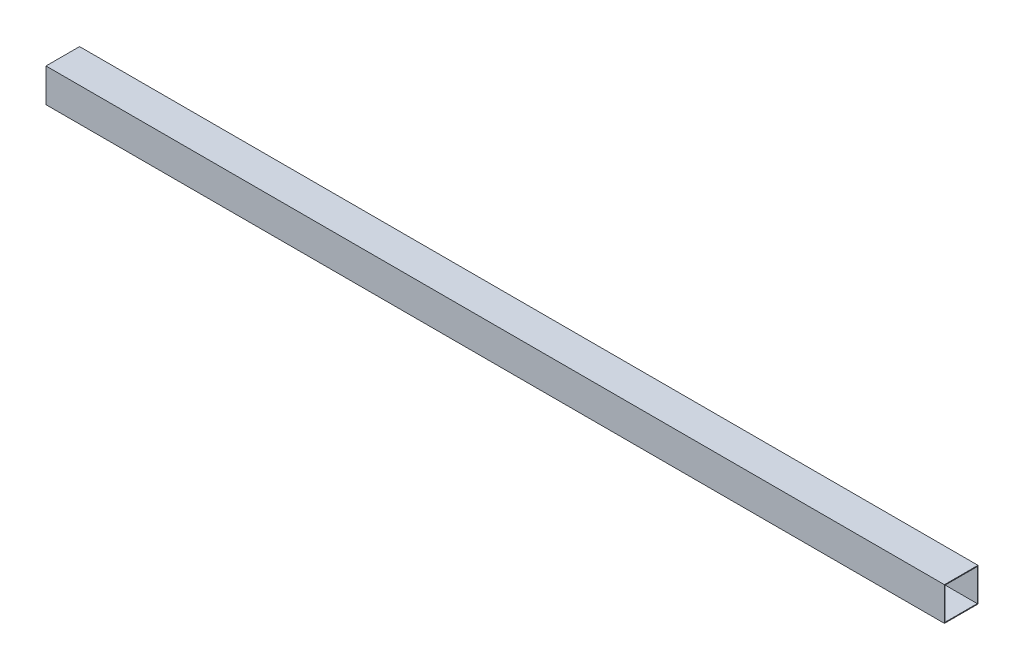
SolidWorks part; units mm, degrees
ref_plane "Alzado" through (0, 0, 0) normal (0, 0, 1) x (1, 0, 0)
ref_plane "Planta" through (0, 0, 0) normal (0, 1, 0) x (1, 0, 0)
ref_plane "Vista lateral" through (0, 0, 0) normal (1, 0, 0) x (0, 0, -1)
sketch "Croquis1" plane through (0, 0, 0) normal (0, 0, 1) x (1, 0, 0)
  line L0 (680, 0) -> (0, 0)
  dimension "D1" = 680
other "Al tube (square) 1 SQ X .022 WALL(1)"
ref_plane "Plano1" through (680, 0, 0) normal (-1, 0, 0) x (0, -1, 0)
sketch "Sketch13" plane through (680, 0, 0) normal (-1, 0, 0) x (0, -1, 0)
  line L0 (-12.1412, -12.1412) -> (-12.1412, 12.1412)
  line L1 (12.1412, 12.1412) -> (-12.1412, 12.1412)
  line L2 (12.1412, 12.1412) -> (12.1412, -12.1412)
  line L3 (-12.1412, -12.1412) -> (12.1412, -12.1412)
  line L4 (-12.7, -12.7) -> (12.7, -12.7)
  line L5 (-12.7, -12.7) -> (-12.7, 12.7)
  line L6 (12.7, 12.7) -> (-12.7, 12.7)
  line L7 (12.7, 12.7) -> (12.7, -12.7)
  line L8 (0, -12.1412) -> (0, -12.7) construction
  line L9 (0, -12.1412) -> (0, 12.1412) construction
  line L10 (0, 12.1412) -> (0, 12.7) construction
  line L11 (12.7, 0) -> (12.1412, 0) construction
  line L12 (12.1412, 0) -> (-12.1412, 0) construction
  line L13 (-12.1412, 0) -> (-12.7, 0) construction
  point P14 (0, 0)
  dimension "Thickness" = 0.5588
  dimension "V_leg" = 25.4
  dimension "H_leg" = 25.4
